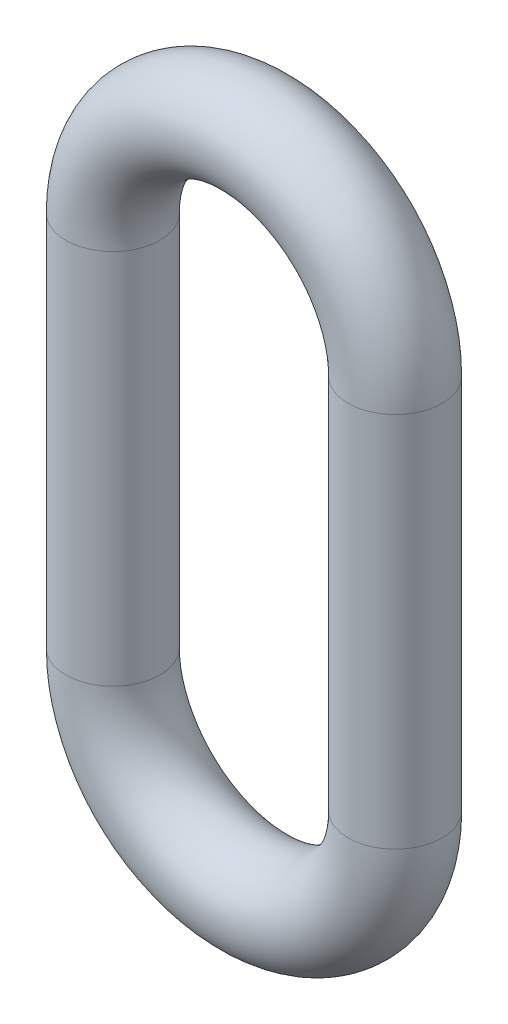
SolidWorks part; units mm, degrees
ref_plane "Спереди" through (0, 0, 0) normal (0, 0, 1) x (1, 0, 0)
ref_plane "Сверху" through (0, 0, 0) normal (0, 1, 0) x (1, 0, 0)
ref_plane "Справа" through (0, 0, 0) normal (1, 0, 0) x (0, 0, -1)
sketch "Эскиз1" plane through (0, 0, 0) normal (0, 0, 1) x (1, 0, 0)
  line L0 (0, 0) -> (0, 12) construction
  line L1 (-4.5, 0) -> (-4.5, 12)
  line L2 (4.5, 0) -> (4.5, 12)
  arc A0 (-4.5, 0) -> (4.5, 0) centre (0, 0) ccw
  arc A1 (4.5, 12) -> (-4.5, 12) centre (0, 12) ccw
  point P3 (0, 6)
  dimension "D1" = 21
  dimension "D2" = 9
sketch "Эскиз2" plane through (0, 0, 0) normal (0, 1, 0) x (1, 0, 0)
  line L0 (-4.5, 0) -> (4.5, 0) construction
  line L1 (-4.5, 0) -> (4.5, 0) construction
  circle A0 centre (-4.5, 0) radius 1.5
  dimension "D1" = 3
sweep "По траектории1" add profiles "Эскиз2" path "Эскиз1"
sketch "Эскиз3" plane through (0, 0, 0) normal (1, 0, 0) x (0, 0, -1)
  circle A0 centre (0, 15) radius 1.5 construction
  circle A1 centre (0, -3) radius 1.5 construction
  arc A2 (1.5, -4.5) -> (-1.5, -4.5) centre (0, -4.5) ccw construction
  arc A3 (-1.5, 16.5) -> (1.5, 16.5) centre (0, 16.5) ccw construction
  dimension "D1" = 3
